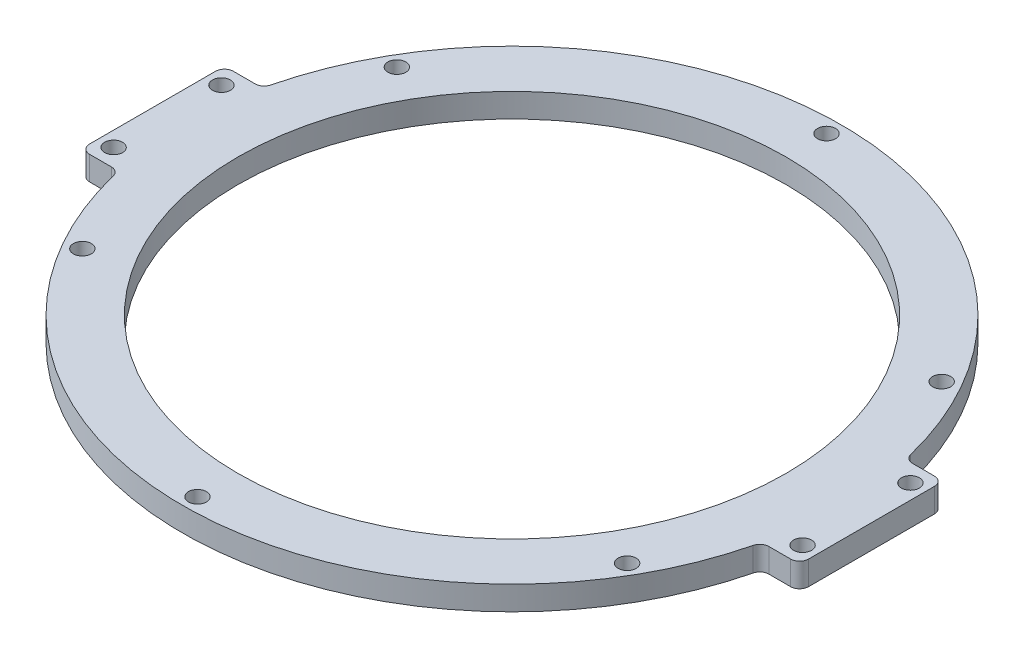
SolidWorks part; units mm, degrees
material "6061 合金"
ref_plane "前视基准面" through (0, 0, 0) normal (0, 0, 1) x (1, 0, 0)
ref_plane "上视基准面" through (0, 0, 0) normal (0, 1, 0) x (1, 0, 0)
ref_plane "右视基准面" through (0, 0, 0) normal (1, 0, 0) x (0, 0, -1)
sketch "草图1" plane through (0, 0, 0) normal (0, 1, 0) x (1, 0, 0)
  line L0 (0, 0) -> (102.5202, 0) construction
  line L1 (0, 0) -> (0, 95.6784) construction
  line L2 (-60, -10.5) -> (-60, 10.5)
  line L3 (-58.5, 12) -> (-54.8635, 12)
  line L4 (-58.5, -12) -> (-54.8635, -12)
  line L5 (58.5, -12) -> (54.8635, -12)
  line L6 (60, -10.5) -> (60, 10.5)
  line L7 (58.5, 12) -> (54.8635, 12)
  circle A0 centre (0, 0) radius 45.75
  arc A1 (-53.4069, -13.1416) -> (53.4069, -13.1416) centre (0, 0) ccw
  arc A2 (53.4069, 13.1416) -> (-53.4069, 13.1416) centre (0, 0) ccw
  arc A3 (58.5, 12) -> (60, 10.5) centre (58.5, 10.5) cw
  arc A4 (58.5, -12) -> (60, -10.5) centre (58.5, -10.5) ccw
  arc A5 (53.4069, -13.1416) -> (54.8635, -12) centre (54.8635, -13.5) cw
  arc A6 (53.4069, 13.1416) -> (54.8635, 12) centre (54.8635, 13.5) ccw
  arc A7 (-58.5, -12) -> (-60, -10.5) centre (-58.5, -10.5) cw
  arc A8 (-58.5, 12) -> (-60, 10.5) centre (-58.5, 10.5) ccw
  arc A9 (-53.4069, -13.1416) -> (-54.8635, -12) centre (-54.8635, -13.5) ccw
  arc A10 (-53.4069, 13.1416) -> (-54.8635, 12) centre (-54.8635, 13.5) cw
  circle A11 centre (0, 0) radius 52.5 construction
  circle A12 centre (0, 52.5) radius 1.5
  circle A13 centre (45.4663, 26.25) radius 1.5
  circle A14 centre (45.4663, -26.25) radius 1.5
  circle A15 centre (0, -52.5) radius 1.5
  circle A16 centre (-45.4663, -26.25) radius 1.5
  circle A17 centre (-45.4663, 26.25) radius 1.5
  circle A18 centre (-57.5, 9) radius 1.5
  circle A19 centre (57.5, 9) radius 1.5
  circle A20 centre (57.5, -9) radius 1.5
  circle A21 centre (-57.5, -9) radius 1.5
  point P9 (-60, 0)
  point P18 (60, 12)
  point P21 (60, -12)
  point P24 (53.6749, -12)
  point P27 (53.6749, 12)
  point P30 (-60, -12)
  point P33 (-60, 12)
  point P36 (-53.6749, -12)
  point P39 (-53.6749, 12)
  point P54 (0, 0)
  dimension "D1" = 91.5
  dimension "D2" = 110
  dimension "D5" = 1.5
  dimension "D6" = 105
  dimension "D7" = 3
  dimension "D9" = 3
  dimension "D10" = 9
  dimension "D11" = 57.5
  dimension "D3" = 24
  dimension "D4" = 60
  dimension "D8" = 6
extrude "凸台-拉伸1" add sketch "草图1" along normal blind 4
